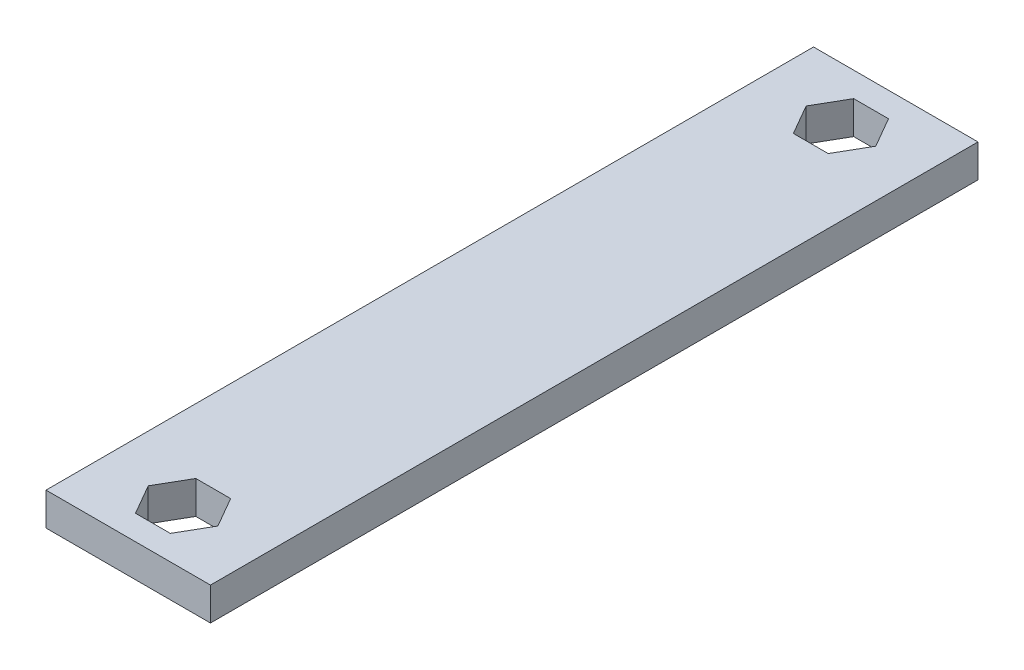
SolidWorks part; units mm, degrees
ref_plane "Front Plane" through (0, 0, 0) normal (0, 0, 1) x (1, 0, 0)
ref_plane "Top Plane" through (0, 0, 0) normal (0, 1, 0) x (1, 0, 0)
ref_plane "Right Plane" through (0, 0, 0) normal (1, 0, 0) x (0, 0, -1)
sketch "Sketch1" plane through (0, 0, 0) normal (0, 1, 0) x (1, 0, 0)
  line L0 (-1000, 35) -> (49000, 35) construction
  line L1 (0, 0) -> (15, 0)
  line L2 (0, 0) -> (0, 70)
  line L3 (0, 70) -> (15, 70)
  line L4 (15, 0) -> (15, 70)
  line L5 (9.0877, 62.25) -> (5.9123, 62.25)
  line L6 (5.9123, 7.75) -> (4.3246, 5)
  line L7 (4.3246, 5) -> (5.9123, 2.25)
  line L8 (5.9123, 2.25) -> (9.0877, 2.25)
  line L9 (9.0877, 2.25) -> (10.6754, 5)
  line L10 (10.6754, 5) -> (9.0877, 7.75)
  line L11 (9.0877, 7.75) -> (5.9123, 7.75)
  line L12 (10.6754, 65) -> (9.0877, 62.25)
  line L13 (9.0877, 67.75) -> (10.6754, 65)
  line L14 (5.9123, 67.75) -> (9.0877, 67.75)
  line L15 (4.3246, 65) -> (5.9123, 67.75)
  line L16 (5.9123, 62.25) -> (4.3246, 65)
  circle A0 centre (7.5, 5) radius 1.75
  circle A1 centre (7.5, 65) radius 1.75
  circle A2 centre (7.5, 5) radius 2.75 construction
  point P8 (7.5, 0)
  point P12 (0, 35)
  dimension "D3" = 3.5
  dimension "D1" = 15
  dimension "D2" = 70
  dimension "D4" = 30
  dimension "D5" = 5.5
extrude "Boss-Extrude1" add sketch "Sketch1" along normal blind 3 contours L1 L4 L3 L2 L11 L10 L9 L8 L7 L6 L5 L16 L15 L14 L13 L12
